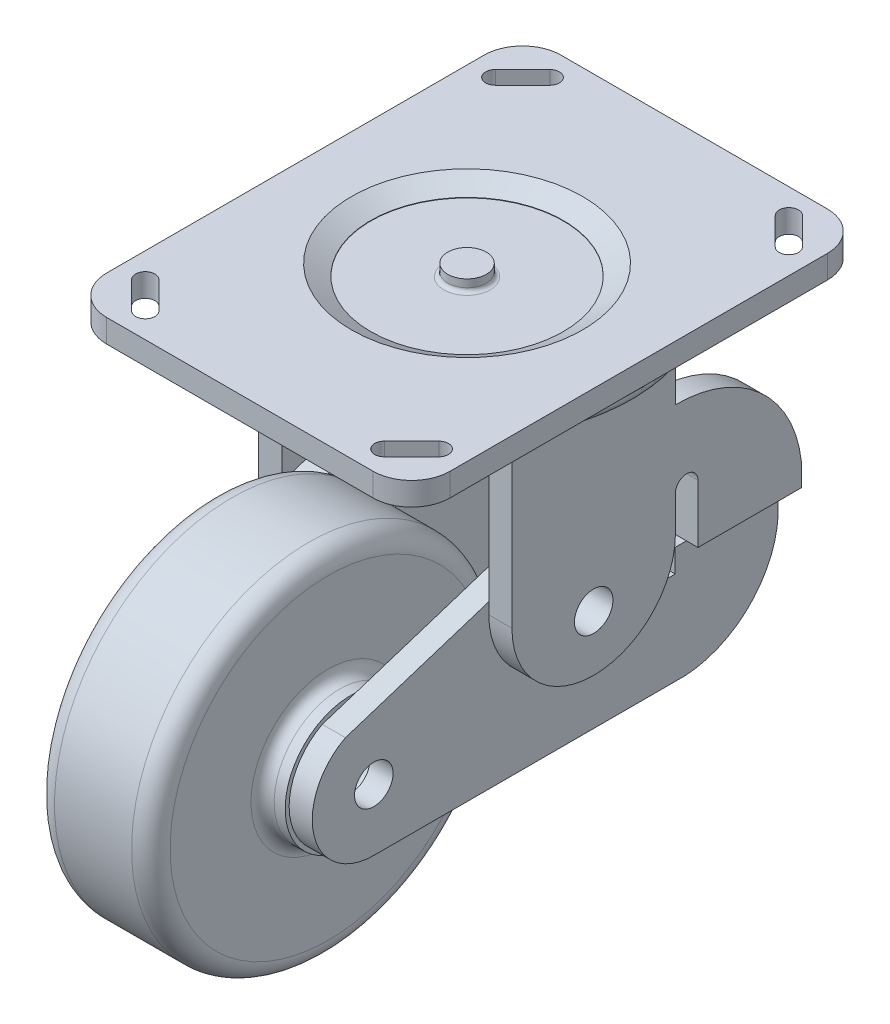
SolidWorks part; units mm, degrees
ref_plane "Front Plane" through (0, 0, 0) normal (0, 0, 1) x (1, 0, 0)
ref_plane "Top Plane" through (0, 0, 0) normal (0, 1, 0) x (1, 0, 0)
ref_plane "Right Plane" through (0, 0, 0) normal (1, 0, 0) x (0, 0, -1)
sketch "Sketch3" plane through (0, 0, 0) normal (0, 1, 0) x (1, 0, 0)
  circle A0 centre (0, 0) radius 39.1208
extrude "Boss-Extrude1" add sketch "Sketch3" along normal blind 6
fillet "Fillet1" radius 5 1 edges at (0, 0, 39.1208)
sketch "Sketch4" plane through (0, 6, 0) normal (0, 1, 0) x (1, 0, 0)
  line L0 (-32.8661, 21.2193) -> (-32.8661, -21.2193)
  line L1 (-32.8661, 21.2193) -> (-26.8661, 21.2193)
  line L2 (-26.8661, 21.2193) -> (-26.8661, -21.2193)
  line L3 (-26.8661, -21.2193) -> (-32.8661, -21.2193)
  circle A0 centre (0, 0) radius 39.1208 construction
extrude "Boss-Extrude2" add sketch "Sketch4" against normal blind 59
sketch "Sketch5" plane through (-32.8661, 0, 0) normal (-1, 0, 0) x (0, 0, 1)
  line L0 (-21.2193, -53) -> (-21.2193, -43.8815)
  line L1 (-21.2193, -53) -> (-21.2193, 5) construction
  line L2 (-21.2193, -24) -> (-21.2193, -43.8815)
  line L3 (-27.0659, -43.8815) -> (-27.0659, -53)
  line L4 (-27.0659, -53) -> (-53.8858, -53)
  arc A0 (-21.2193, -24) -> (-53.8858, -53) centre (-21.4458, -56.6431) ccw
  arc A1 (-21.2193, -43.8815) -> (-27.0659, -43.8815) centre (-24.1426, -43.8815) ccw
  line M3 (-21.2193, 5) -> (-21.2193, -53)
extrude "Boss-Extrude3" add sketch "Sketch5" against normal blind 6 contours A1 A0 L4 L3 M3
sketch "Sketch6" plane through (-32.8661, 0, 0) normal (-1, 0, 0) x (0, 0, 1)
  line L0 (-21.2193, -53) -> (21.2193, -53)
  arc A0 (-21.2193, -53) -> (21.2193, -53) centre (0, -53) ccw
  line M9 (-21.2193, -53) -> (21.2193, -53)
extrude "Boss-Extrude4" add sketch "Sketch6" against normal blind 6 contours A0 M9
mirror "Mirror1" about plane through (0, 0, 0) normal (1, 0, 0) of "Boss-Extrude2"
mirror "Mirror2" about plane through (0, 0, 0) normal (1, 0, 0) of "Boss-Extrude4", "Boss-Extrude3"
sketch "Sketch8" plane through (0, 0, 0) normal (1, 0, 0) x (0, 0, -1)
  line L0 (0, 6) -> (8.2248, 6)
  line L1 (39.1208, 6) -> (-39.1208, 6) construction
  line L3 (8.2248, 12) -> (28.3064, 12)
  line L5 (0, 6) -> (0, 9)
  arc A0 (8.2248, 6) -> (28.3064, 12) centre (0.314, 69.0828) ccw
  arc A1 (0, 9) -> (8.2248, 12) centre (0.2277, 21.1503) ccw
revolve "Revolve1" add sketch "Sketch8" angle 360 about L5
fillet "Fillet2" radius 5 1 edges at (0, 12, -8.2248)
sketch "Sketch9" plane through (0, 6, 0) normal (0, 1, 0) x (1, 0, 0)
  line L1 (35.6994, -52.9389) -> (-35.6994, -52.9389)
  line L2 (35.6994, -52.9389) -> (35.6994, 52.9389)
  line L3 (35.6994, 52.9389) -> (-35.6994, 52.9389)
  line L4 (-35.6994, -52.9389) -> (-35.6994, 52.9389)
  line L5 (35.6994, -52.9389) -> (-35.6994, 52.9389) construction
  line L6 (35.6994, 52.9389) -> (-35.6994, -52.9389) construction
  circle A0 centre (0, 0) radius 14.1186
extrude "Boss-Extrude10" add sketch "Sketch9" along normal blind 6
sketch "Sketch10" plane through (0, 12, 0) normal (0, 1, 0) x (1, 0, 0)
  circle A0 centre (0, 0) radius 3.6434
extrude "Cut-Extrude1" cut sketch "Sketch10" against normal blind 21
sketch "Sketch11" plane through (0, -53, 0) normal (0, -1, 0) x (1, 0, 0)
  line L1 (-32.8661, -27.0659) -> (32.8661, -27.0659)
  line L2 (-32.8661, -27.0659) -> (-32.8661, -53.8858)
  line L3 (-32.8661, -53.8858) -> (32.8661, -53.8858)
  line L4 (32.8661, -27.0659) -> (32.8661, -53.8858)
extrude "Boss-Extrude11" add sketch "Sketch11" along normal blind 6
sketch "Sketch12" plane through (26.8661, 0, 0) normal (-1, 0, 0) x (0, 0, 1)
  line L0 (-53.8858, -59) -> (-53.8858, -62)
  line L1 (-53.8858, -62) -> (-27.0659, -62)
  line L2 (-27.0659, -62) -> (-27.0659, -59)
  line L3 (-27.0659, -59) -> (-53.8858, -59)
  line L4 (-53.8858, -62) -> (-53.8858, -68)
  line L5 (-53.8858, -68) -> (-27.0659, -68)
  line L6 (-27.0659, -68) -> (-27.0659, -62)
  line L8 (-27.0659, -92.152) -> (51.0683, -92.152)
  line L10 (58.4306, -62) -> (0, -43.2207)
  line L11 (0, -43.2207) -> (-19.6543, -68)
  line L12 (-19.6543, -68) -> (-27.0659, -68)
  arc A1 (51.0683, -92.152) -> (58.4306, -62) centre (51.0683, -76.1771) ccw
  arc A2 (-53.8858, -68) -> (-27.0659, -92.152) centre (-28.3999, -66.6661) ccw
  arc M9 (-21.2193, -53) -> (21.2193, -53) centre (0, -53) ccw
  line M10 (21.2193, -53) -> (21.2193, 0.0013)
extrude "Boss-Extrude13" add sketch "Sketch12" along normal blind 6 contours L5 A2 L8 A1 L10 L11 L12 M10 M9 | L10 L11 M9 M10
mirror "Mirror3" about plane through (0, 0, 0) normal (1, 0, 0) of "Boss-Extrude13"
sketch "Sketch13" plane through (0, -68, 0) normal (0, 1, 0) x (1, 0, 0)
  line L0 (26.8661, 53.8858) -> (26.8661, 19.6543) construction
  line L1 (-26.8661, 53.8858) -> (26.8661, 53.8858)
  line L2 (-26.8661, 53.8858) -> (-26.8661, 19.6543)
  line L3 (-26.8661, 19.6543) -> (26.8661, 19.6543)
  line L4 (26.8661, 53.8858) -> (26.8661, 19.6543)
  line L5 (26.8661, 27.0659) -> (26.8661, -51.0683) construction
extrude "Boss-Extrude14" add sketch "Sketch13" along normal blind 6
sketch "Sketch15" plane through (-26.8661, 0, 0) normal (-1, 0, 0) x (0, 0, 1)
  line L0 (-19.6543, -68) -> (-27.1496, -68)
  line L1 (-27.1496, -68) -> (-27.1496, -62)
  line L2 (-53.8858, -62) -> (-19.6543, -62) construction
  line L3 (-27.1496, -62) -> (-19.6543, -62)
  line L4 (-19.6543, -62) -> (-19.6543, -68)
extrude "Cut-Extrude2" cut sketch "Sketch15" against normal blind 96
sketch "Sketch16" plane through (0, -62, 0) normal (0, 1, 0) x (1, 0, 0)
  circle A0 centre (0, 40.5177) radius 13.4324
extrude "Boss-Extrude16" add sketch "Sketch16" along normal blind 3
sketch "Sketch21" plane through (0, -53, 0) normal (0, 1, 0) x (1, 0, 0)
  line L0 (0, 53.8858) -> (0, 27.0659)
  line L1 (-26.8661, 53.8858) -> (26.8661, 53.8858) construction
  line L2 (26.8661, 27.0659) -> (-26.8661, 27.0659) construction
  circle A0 centre (0, 40.4758) radius 5
sketch "Sketch22" plane through (32.8661, 0, 0) normal (1, 0, 0) x (0, 0, -1)
  circle A0 centre (0, -59.7766) radius 5
sketch "Sketch24" plane through (-26.8661, 0, 0) normal (-1, 0, 0) x (0, 0, 1)
  circle A0 centre (51.0683, -76.1771) radius 5
extrude "Cut-Extrude7" cut sketch "Sketch24" against normal blind 65
extrude "Cut-Extrude8" cut sketch "Sketch22" against normal blind 107
sketch "Sketch26" plane through (0, 0, 0) normal (1, 0, 0) x (0, 0, -1)
  line L1 (-51.0683, -92.152) -> (-51.0683, -122.1771) construction
  line L2 (-36.1571, 12) -> (-36.1571, -92.152) construction
  line L3 (-52.9389, 12) -> (52.9389, 12) construction
  line L4 (27.0659, -92.152) -> (-51.0683, -92.152) construction
  circle A0 centre (-51.0683, -76.1771) radius 46
sketch "Sketch27" plane through (0, 0, 0) normal (1, 0, 0) x (0, 0, -1)
  line L0 (0, 12) -> (0, -8)
  line L1 (-52.9389, 12) -> (52.9389, 12) construction
  line L3 (-62.9265, 20.326) -> (63.0885, 20.326)
  line L4 (-62.9265, 20.326) -> (-62.9265, -8)
  line L5 (-62.9265, -8) -> (63.0885, -8)
  line L6 (63.0885, 20.326) -> (63.0885, -8)
extrude "Cut-Extrude9" cut sketch "Sketch27" against normal mid plane 107
sketch "Sketch28" plane through (0, -8, 0) normal (0, 1, 0) x (1, 0, 0)
  line L0 (-32.8661, 0) -> (26.8661, 0) construction
  line L1 (-32.8661, 21.2193) -> (-32.8661, -21.2193) construction
  line L2 (26.8661, -21.2193) -> (26.8661, 21.2193) construction
  line L3 (0, 27.0659) -> (0, -21.3494) construction
  line L4 (0, -97.0683) -> (0, -5.0683) construction
  circle A0 centre (0, 0) radius 43.7326
extrude "Boss-Extrude17" add sketch "Sketch28" along normal blind 4
fillet "Fillet3" radius 3 1 edges at (0, -8, 43.7326)
fillet "Fillet4" radius 1 8 edges at (-29.8661, -8, 21.2193) (-32.8661, -8, 0) (-29.8661, -8, -21.2193) (-26.8661, -8, 0) (29.8661, -8, -21.2193) (26.8661, -8, 0) (29.8661, -8, 21.2193) (32.8661, -8, 0)
sketch "Sketch29" plane through (0, -4, 0) normal (0, 1, 0) x (1, 0, 0)
  line L1 (44.5605, -58.9577) -> (-44.5605, -58.9577)
  line L2 (44.5605, -58.9577) -> (44.5605, 58.9577)
  line L3 (44.5605, 58.9577) -> (-44.5605, 58.9577)
  line L4 (-44.5605, -58.9577) -> (-44.5605, 58.9577)
  line L5 (44.5605, -58.9577) -> (-44.5605, 58.9577) construction
  line L6 (44.5605, 58.9577) -> (-44.5605, -58.9577) construction
  point P0 (0, 0)
extrude "Boss-Extrude18" add sketch "Sketch29" along normal blind 6
fillet "Fillet5" radius 10 4 edges at (-44.5605, -1, 58.9577) (-44.5605, -1, -58.9577) (44.5605, -1, -58.9577) (44.5605, -1, 58.9577)
extrude "Boss-Extrude19" add sketch "Sketch26" along normal mid plane 30 separate body
sketch "Sketch30" plane through (15, 0, 0) normal (1, 0, 0) x (0, 0, -1)
  circle A0 centre (-51.0683, -76.1771) radius 17
extrude "Boss-Extrude20" add sketch "Sketch30" along normal up to surface (5.8661 mm away)
fillet "Fillet6" radius 5 2 edges at (-15, -76.1771, 5.0683) (15, -76.1771, 5.0683)
ref_plane "Plane1" through (0, 0, 0) normal (1, 0, 0) x (0, 0, -1)
sketch "Sketch31" plane through (-15, 0, 0) normal (-1, 0, 0) x (0, 0, 1)
  circle A0 centre (51.0683, -76.1771) radius 17
extrude "Boss-Extrude21" add sketch "Sketch31" along normal up to surface (5.8661 mm away)
extrude "Cut-Extrude10" cut sketch "Sketch21" against normal blind 30 contours A0
sketch "Sketch32" plane through (-20.8661, 0, 0) normal (-1, 0, 0) x (0, 0, 1)
  circle A0 centre (51.0683, -76.1771) radius 5.543
extrude "Cut-Extrude11" cut sketch "Sketch32" against normal up to surface (41.7321 mm away)
fillet "Fillet7" radius 3 2 edges at (15, -76.1771, 34.0683) (-15, -76.1771, 34.0683)
sketch "Sketch35" plane through (0, 0, 0) normal (1, 0, 0) x (0, 0, -1)
  line L0 (-29.5532, 2) -> (-29.5532, -92.152) construction
  line L1 (-48.9577, 2) -> (48.9577, 2) construction
  line L2 (27.0659, -92.152) -> (-51.0683, -92.152) construction
  line L4 (-23.3662, -76.1771) -> (-23.3662, -92.152) construction
sketch "Sketch36" plane through (0, 2, 0) normal (0, 1, 0) x (1, 0, 0)
  circle A0 centre (0, 0) radius 25
extrude "Cut-Extrude12" cut sketch "Sketch36" against normal blind 3
chamfer "Chamfer1" distance 5 angle 30 1 edges at (0, 2, 25)
sketch "Sketch37" plane through (0, 2, 0) normal (0, 1, 0) x (1, 0, 0)
  line L0 (0, -78.3784) -> (0, 78.3784) construction
  line L3 (-87.4639, 0) -> (87.4639, 0) construction
  line L4 (31.025, 52.4933) -> (38.096, 45.4222) construction
  line L7 (-31.025, 52.4933) -> (-38.096, 45.4222) construction
  line L10 (32.7927, 54.261) -> (39.8638, 47.19)
  line L13 (29.2572, 50.7255) -> (36.3283, 43.6544)
  line L14 (-32.7927, 54.261) -> (-39.8638, 47.19)
  line L15 (-29.2572, 50.7255) -> (-36.3283, 43.6544)
  line L16 (31.025, -52.4933) -> (38.096, -45.4222) construction
  line L17 (32.7927, -54.261) -> (39.8638, -47.19)
  line L18 (29.2572, -50.7255) -> (36.3283, -43.6544)
  line L19 (-31.025, -52.4933) -> (-38.096, -45.4222) construction
  line L20 (-32.7927, -54.261) -> (-39.8638, -47.19)
  line L21 (-29.2572, -50.7255) -> (-36.3283, -43.6544)
  arc A12 (32.7927, 54.261) -> (29.2572, 50.7255) centre (31.025, 52.4933) ccw
  arc A13 (36.3283, 43.6544) -> (39.8638, 47.19) centre (38.096, 45.4222) ccw
  arc A14 (-32.7927, 54.261) -> (-29.2572, 50.7255) centre (-31.025, 52.4933) cw
  arc A15 (-36.3283, 43.6544) -> (-39.8638, 47.19) centre (-38.096, 45.4222) cw
  arc A16 (32.7927, -54.261) -> (29.2572, -50.7255) centre (31.025, -52.4933) cw
  arc A17 (36.3283, -43.6544) -> (39.8638, -47.19) centre (38.096, -45.4222) cw
  arc A18 (-32.7927, -54.261) -> (-29.2572, -50.7255) centre (-31.025, -52.4933) ccw
  arc A19 (-36.3283, -43.6544) -> (-39.8638, -47.19) centre (-38.096, -45.4222) ccw
  point P6 (0, 0)
  point P9 (0, 0)
  point P18 (-34.5605, 48.9577)
  point P20 (34.5605, 48.9577)
  point P29 (34.5605, -48.9577)
  point P42 (-34.5605, -48.9577)
extrude "Cut-Extrude13" cut sketch "Sketch37" against normal blind 8
sketch "Sketch38" plane through (0, -1, 0) normal (0, 1, 0) x (1, 0, 0)
  circle A0 centre (0, 0) radius 5
extrude "Boss-Extrude24" add sketch "Sketch38" along normal blind 3
fillet "Fillet8" radius 1 1 edges at (0, -1, 5)
sketch "Sketch40" plane through (0, 2, 0) normal (0, 1, 0) x (1, 0, 0)
  line L11 (-34.5605, 48.9577) -> (34.5605, 48.9577) construction
  line L12 (34.5605, 48.9577) -> (34.5605, -48.9577) construction
  circle A0 centre (-34.5605, 48.9577) radius 2.5
  circle A1 centre (34.5605, 48.9577) radius 2.5
  circle A2 centre (34.5605, -48.9577) radius 2.5
  circle A3 centre (-34.5605, -48.9577) radius 2.5
  dimension "D1" = 5
  dimension "D2" = 5
  dimension "D3" = 5
  dimension "D4" = 5
